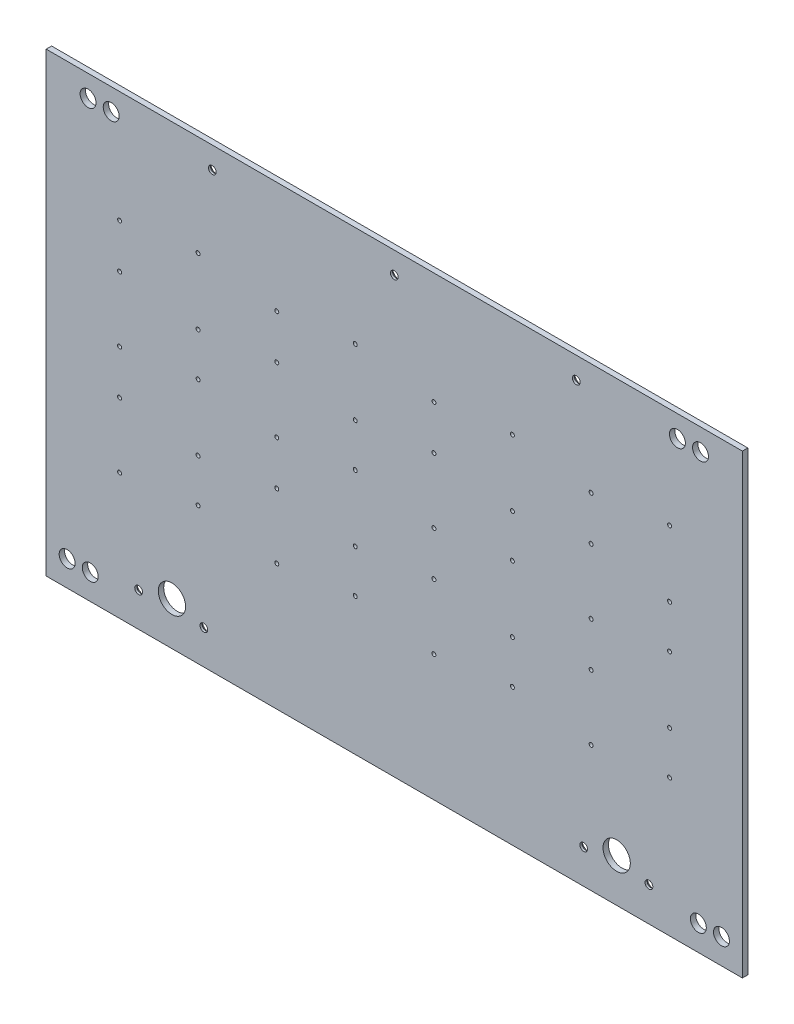
SolidWorks part; units mm, degrees
material "ABS"
ref_plane "X-Y Datum" through (0, 0, 0) normal (0, 0, 1) x (1, 0, 0)
ref_plane "X-Z Datum" through (0, 0, 0) normal (0, 1, 0) x (1, 0, 0)
ref_plane "Y-Z Datum" through (0, 0, 0) normal (1, 0, 0) x (0, 0, -1)
sketch "Sketch1" plane through (0, 0, 0) normal (0, 0, 1) x (1, 0, 0)
  line L0 (-153.025, 98.7125) -> (-153.025, -98.7125)
  line L1 (-153.025, 98.7125) -> (153.025, 98.7125)
  line L2 (-153.025, 98.7125) -> (-153.025, -98.7125)
  line L3 (-153.025, -98.7125) -> (153.025, -98.7125)
  line L4 (153.025, 98.7125) -> (153.025, -98.7125)
  line L5 (-153.025, 98.7125) -> (153.025, -98.7125) construction
  line L6 (-153.025, -98.7125) -> (153.025, 98.7125) construction
  line L7 (-153.025, -98.7125) -> (153.025, -98.7125)
  line L8 (153.025, 98.7125) -> (153.025, -98.7125)
  line L9 (-153.025, 98.7125) -> (153.025, 98.7125)
  circle A0 centre (-142.25, -87.9375) radius 10.775
  circle A1 centre (-118.25, -87.9375) radius 10.775 construction
  circle A2 centre (-130.25, -64.9375) radius 10.775
  point P0 (0, 0)
  dimension "D1" = 21.55
  dimension "D2" = 24
  dimension "D3" = 23
  dimension "D4" = 12
  dimension "D5" = 197.425
  dimension "D6" = 306.05
  dimension "D7" = 0
extrude "Boss-Extrude1" add sketch "Sketch1" along normal blind 2.3813 contours A0 L3 L4 L1 L2 A2 | A2 | A0 | A0 L2 L3 | L9 L0 L7 L8 L1 L4 L3 L2
sketch "Sketch9" plane through (0, 98.7125, 0) normal (0, 1, 0) x (1, 0, 0)
  line L4 (153.025, 0) -> (-153.025, 0)
  line L5 (-153.025, 0) -> (-153.025, -2.3813)
  line L6 (-153.025, -2.3813) -> (153.025, -2.3813)
  line L7 (153.025, -2.3813) -> (153.025, 0)
  line L8 (153.025, 0) -> (-153.025, 0)
  line L9 (-153.025, 0) -> (-153.025, -2.3813)
  line L10 (-153.025, -2.3813) -> (153.025, -2.3813)
  line L11 (153.025, -2.3813) -> (153.025, 0)
  dimension "D1" = 0
extrude "Boss-Extrude2" add sketch "Sketch9" along normal blind 3.175
sketch "Sketch10" plane through (0, 0, 0) normal (0, 0, -1) x (-1, 0, 0)
  circle A0 centre (-134.61, 92.3625) radius 3.5
  circle A1 centre (-124.45, 92.3625) radius 3.5
  circle A2 centre (-143.8175, -87.5375) radius 3.5
  circle A3 centre (-133.6575, -87.5375) radius 3.5
  point P1 (-133.6575, -87.5375)
  dimension "D1" = 7
extrude "Cut-Extrude1" cut sketch "Sketch10" against normal through all
mirror "Mirror1" about plane through (0, 0, 0) normal (1, 0, 0) of "Cut-Extrude1"
sketch "Sketch11" plane through (0, 0, 0) normal (0, 0, -1) x (-1, 0, 0)
  point P0 (-111.94, -83.7125)
  point P1 (-83.25, -83.7125)
  point P5 (-80, 92.3625)
  point P7 (0, 92.3625)
  point P9 (80, 92.3625)
  point P13 (112.402, -83.7125)
  point P15 (83.712, -83.7125)
hole_wizard "CSK for M3 Flat Head Machine Screw1" positions "Sketch11" profile "Sketch12" countersink size "M3" standard "ANSI Metric" end condition through all
sketch "Sketch12" plane through (111.94, -83.7125, 0) normal (1, 0, 0) x (0, 1, 0)
  line L0 (0, 0) -> (0, 2.3812)
  line L1 (0, 2.3812) -> (1.7, 2.3812)
  line L2 (1.7, 2.3812) -> (1.7, 1.45)
  line L3 (1.7, 1.45) -> (3.15, 0)
  line L5 (3.15, 0) -> (0, 0)
  line L6 (-1.7, 1.45) -> (-3.15, 0) construction
  line L11 (0, -6.35) -> (0, 107.95) construction
  dimension "Thru Hole Dia." = 3.4
  dimension "Thru Hole Depth" = 2.3813
  dimension "Near C'Sink Dia." = 6.3
  dimension "Near C'Sink Angle" = 90
sketch "Sketch13" plane through (0, 0, 0) normal (0, 0, -1) x (-1, 0, 0)
  circle A0 centre (-97.75, -79.7125) radius 6 construction
  circle A1 centre (97.75, -79.7125) radius 6 construction
  circle A2 centre (-97.75, -79.7125) radius 6
  circle A3 centre (97.75, -79.7125) radius 6
extrude "Cut-Extrude2" cut sketch "Sketch13" against normal through all
sketch "Sketch14" plane through (0, 0, 0) normal (0, 0, -1) x (-1, 0, 0)
  line L4 (153.025, -98.7125) -> (153.025, 101.8875)
  line L5 (153.025, 101.8875) -> (-153.025, 101.8875)
  line L6 (-153.025, 101.8875) -> (-153.025, -98.7125)
  line L7 (-153.025, -98.7125) -> (153.025, -98.7125)
  line L8 (153.025, -98.7125) -> (153.025, 101.8875)
  line L9 (153.025, 101.8875) -> (-153.025, 101.8875)
  line L10 (-153.025, 101.8875) -> (-153.025, -98.7125)
  line L11 (-153.025, -98.7125) -> (153.025, -98.7125)
  dimension "D1" = 0
sketch "Sketch15" plane through (0, 0, 0) normal (0, 0, -1) x (-1, 0, 0)
  circle A0 centre (86.25, 9.5954) radius 0.875 construction
  circle A1 centre (-51.926, 57.5964) radius 0.875 construction
  circle A2 centre (-17.426, 52.7814) radius 0.875 construction
  circle A3 centre (-86.514, -43.2204) radius 0.875 construction
  circle A4 centre (-121.014, -38.4055) radius 0.875 construction
  circle A5 centre (-121.014, -19.4695) radius 0.875 construction
  circle A6 centre (-86.514, -14.6546) radius 0.875 construction
  circle A7 centre (-86.514, 4.7805) radius 0.875 construction
  circle A8 centre (-121.014, 9.5954) radius 0.875 construction
  circle A9 centre (-121.014, 28.5365) radius 0.875 construction
  circle A10 centre (-86.514, 33.3514) radius 0.875 construction
  circle A11 centre (-86.514, 52.7814) radius 0.875 construction
  circle A12 centre (-121.014, 57.5964) radius 0.875 construction
  circle A13 centre (-51.926, 28.5365) radius 0.875 construction
  circle A14 centre (-17.426, 33.3514) radius 0.875 construction
  circle A15 centre (-17.426, 4.7805) radius 0.875 construction
  circle A16 centre (-51.926, 9.5954) radius 0.875 construction
  circle A17 centre (-51.926, -19.4695) radius 0.875 construction
  circle A18 centre (-17.426, -14.6546) radius 0.875 construction
  circle A19 centre (-51.926, -38.4055) radius 0.875 construction
  circle A20 centre (-17.426, -43.2204) radius 0.875 construction
  circle A21 centre (17.162, -38.4055) radius 0.875 construction
  circle A22 centre (17.162, -19.4695) radius 0.875 construction
  circle A23 centre (51.662, -14.6546) radius 0.875 construction
  circle A24 centre (17.162, 9.5954) radius 0.875 construction
  circle A25 centre (51.662, 4.7805) radius 0.875 construction
  circle A26 centre (51.662, 33.3514) radius 0.875 construction
  circle A27 centre (17.162, 28.5365) radius 0.875 construction
  circle A28 centre (17.162, 57.5964) radius 0.875 construction
  circle A29 centre (51.662, 52.7814) radius 0.875 construction
  circle A30 centre (86.25, 57.5964) radius 0.875 construction
  circle A31 centre (120.75, 52.7814) radius 0.875 construction
  circle A32 centre (86.25, 28.5365) radius 0.875 construction
  circle A33 centre (120.75, 33.3514) radius 0.875 construction
  circle A34 centre (51.662, -43.2204) radius 0.875 construction
  circle A35 centre (86.25, -38.4055) radius 0.875 construction
  circle A36 centre (86.25, -19.4695) radius 0.875 construction
  circle A37 centre (120.75, 4.7805) radius 0.875 construction
  circle A38 centre (120.75, -14.6546) radius 0.875 construction
  circle A39 centre (120.75, -43.2204) radius 0.875 construction
  circle A40 centre (86.25, 9.5954) radius 0.875
  circle A41 centre (-51.926, 57.5964) radius 0.875
  circle A42 centre (-17.426, 52.7814) radius 0.875
  circle A43 centre (-86.514, -43.2204) radius 0.875
  circle A44 centre (-121.014, -38.4055) radius 0.875
  circle A45 centre (-121.014, -19.4695) radius 0.875
  circle A46 centre (-86.514, -14.6546) radius 0.875
  circle A47 centre (-86.514, 4.7805) radius 0.875
  circle A48 centre (-121.014, 9.5954) radius 0.875
  circle A49 centre (-121.014, 28.5365) radius 0.875
  circle A50 centre (-86.514, 33.3514) radius 0.875
  circle A51 centre (-86.514, 52.7814) radius 0.875
  circle A52 centre (-121.014, 57.5964) radius 0.875
  circle A53 centre (-51.926, 28.5365) radius 0.875
  circle A54 centre (-17.426, 33.3514) radius 0.875
  circle A55 centre (-17.426, 4.7805) radius 0.875
  circle A56 centre (-51.926, 9.5954) radius 0.875
  circle A57 centre (-51.926, -19.4695) radius 0.875
  circle A58 centre (-17.426, -14.6546) radius 0.875
  circle A59 centre (-51.926, -38.4055) radius 0.875
  circle A60 centre (-17.426, -43.2204) radius 0.875
  circle A61 centre (17.162, -38.4055) radius 0.875
  circle A62 centre (17.162, -19.4695) radius 0.875
  circle A63 centre (51.662, -14.6546) radius 0.875
  circle A64 centre (17.162, 9.5954) radius 0.875
  circle A65 centre (51.662, 4.7805) radius 0.875
  circle A66 centre (51.662, 33.3514) radius 0.875
  circle A67 centre (17.162, 28.5365) radius 0.875
  circle A68 centre (17.162, 57.5964) radius 0.875
  circle A69 centre (51.662, 52.7814) radius 0.875
  circle A70 centre (86.25, 57.5964) radius 0.875
  circle A71 centre (120.75, 52.7814) radius 0.875
  circle A72 centre (86.25, 28.5365) radius 0.875
  circle A73 centre (120.75, 33.3514) radius 0.875
  circle A74 centre (51.662, -43.2204) radius 0.875
  circle A75 centre (86.25, -38.4055) radius 0.875
  circle A76 centre (86.25, -19.4695) radius 0.875
  circle A77 centre (120.75, 4.7805) radius 0.875
  circle A78 centre (120.75, -14.6546) radius 0.875
  circle A79 centre (120.75, -43.2204) radius 0.875
extrude "Cut-Extrude3" cut sketch "Sketch15" against normal through all
